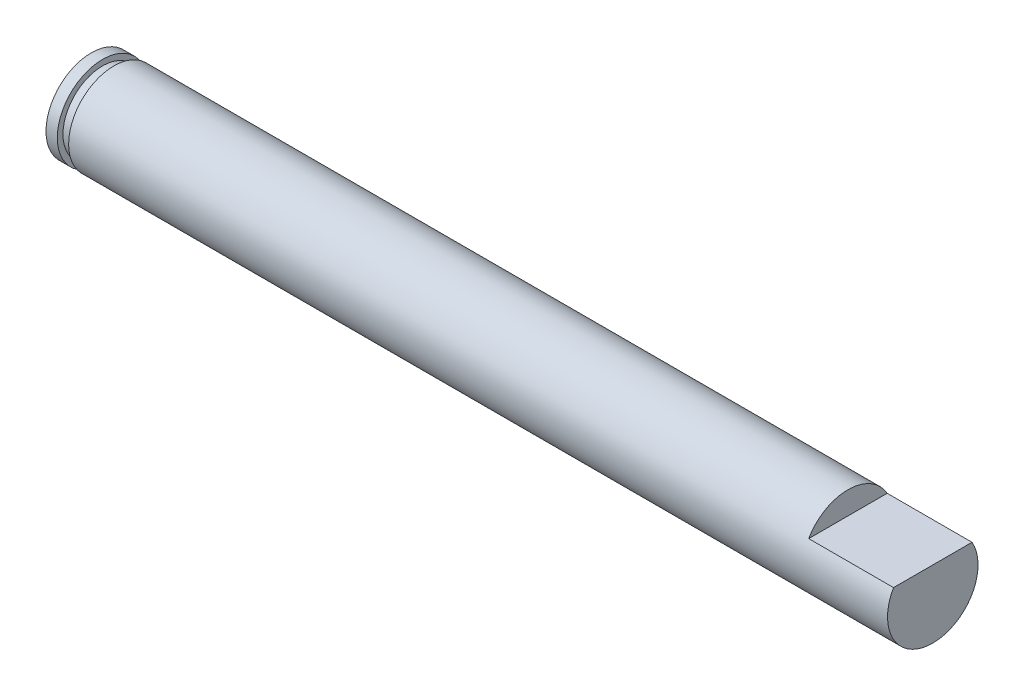
SolidWorks part; units mm, degrees
ref_plane "Front Plane" through (0, 0, 0) normal (0, 0, 1) x (1, 0, 0)
ref_plane "Top Plane" through (0, 0, 0) normal (0, 1, 0) x (1, 0, 0)
ref_plane "Right Plane" through (0, 0, 0) normal (1, 0, 0) x (0, 0, -1)
sketch "Sketch2" plane through (0, 0, 0) normal (1, 0, 0) x (0, 0, -1)
  circle A0 centre (0, 0) radius 4
  dimension "D1" = 8
extrude "Boss-Extrude1" add sketch "Sketch2" along normal up to surface (66.9 mm away)
sketch "Sketch3" plane through (66.9, 0, 0) normal (1, 0, 0) x (0, 0, -1)
  line L0 (-3.4699, 1.99) -> (3.4699, 1.99)
  circle A0 centre (0, 0) radius 4 construction
  arc A1 (-3.4699, 1.99) -> (3.4699, 1.99) centre (0, 0) ccw
  dimension "D1" = 1.99
extrude "Boss-Extrude2" add sketch "Sketch3" along normal blind 7.5
sketch "Sketch4" plane through (0, 0, 0) normal (0, 0, 1) x (1, 0, 0)
  line L0 (66.9, 4) -> (0, 4) construction
  line L1 (1, 4) -> (2, 4)
  line L2 (1, 4) -> (1, 3.5)
  line L3 (1, 3.5) -> (2, 3.5)
  line L4 (2, 4) -> (2, 3.5)
  line L5 (0, -4.4) -> (0, 4.4) construction
  line L6 (0, 0) -> (2.54, 0) construction
  dimension "D1" = 1
  dimension "D2" = 0.5
  dimension "D3" = 1
  dimension "D4" = 2.54
revolve "Cut-Revolve1" cut sketch "Sketch4" angle 360 about L6
